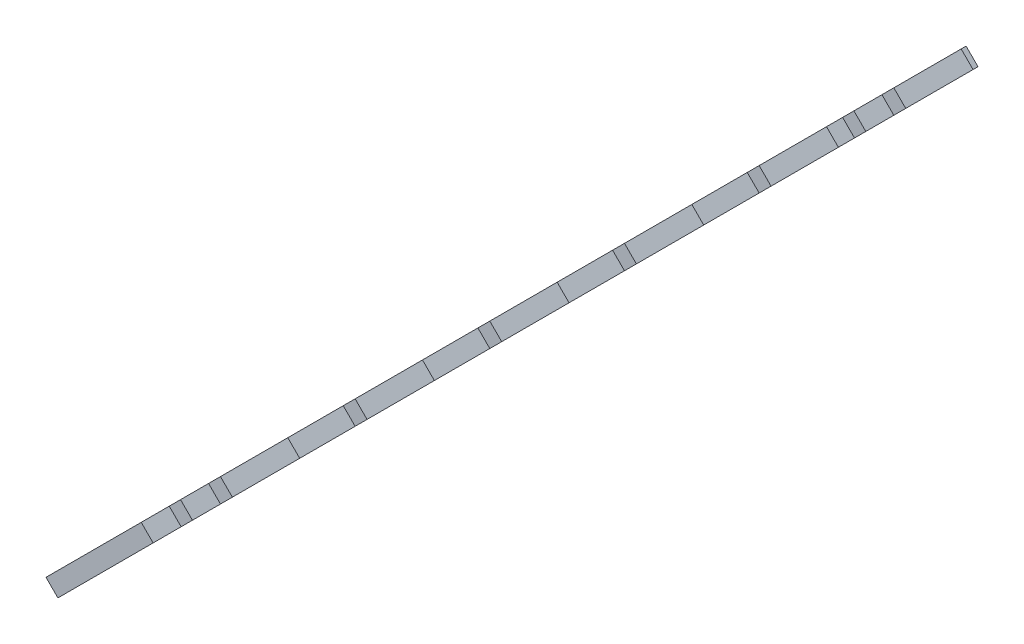
SolidWorks part; units mm, degrees
ref_plane "Front Plane" through (0, 0, 0) normal (0, 0, 1) x (1, 0, 0)
ref_plane "Top Plane" through (0, 0, 0) normal (0, 1, 0) x (1, 0, 0)
ref_plane "Right Plane" through (0, 0, 0) normal (1, 0, 0) x (0, 0, -1)
sketch "Sketch1" plane through (0, 0, 0) normal (0, 0, 1) x (1, 0, 0)
  line L0 (91.6648, 29.3027) -> (52.5461, -9.816) construction
  line L2 (78.5772, 20.7053) -> (74.1015, 16.2295) construction
  line L3 (78.5917, 11.7394) -> (83.0674, 16.2151) construction
  line L4 (37.7171, 7.6839) -> (33.2269, 12.174)
  line L5 (37.7171, 7.6839) -> (73.6381, 43.6049)
  line L6 (33.2269, 12.174) -> (69.148, 48.095)
  line L7 (73.6381, 43.6049) -> (69.148, 48.095)
  line L8 (110.4572, 6.7859) -> (74.5361, -29.1352) construction
  line L9 (74.5361, -29.1352) -> (70.046, -24.645) construction
  line L10 (105.967, 11.276) -> (70.046, -24.645) construction
extrude "Boss-Extrude1" add sketch "Sketch1" along normal up to surface (304.8 mm away)
sketch "Sketch2" plane through (58.6215, 58.6215, 0) normal (0.7071, 0.7071, 0) x (0, 0, -1)
  line L0 (-304.8, -21.2367) -> (0, -21.2367) construction
  line L1 (-279.4, -21.2367) -> (-254, -21.2367)
  line L2 (-279.4, -21.2367) -> (-279.4, -14.8867)
  line L3 (-279.4, -14.8867) -> (-254, -14.8867)
  line L4 (-254, -21.2367) -> (-254, -14.8867)
  line L5 (-304.8, -14.8867) -> (0, -14.8867) construction
  dimension "D1" = 25.4
  dimension "D2" = 25.4
extrude "Boss-Extrude2" add sketch "Sketch2" along normal blind 6.35
pattern_linear "LPattern1" count 6 spacing 50.8 along (0, 0, -1) of "Boss-Extrude2"
sketch "Sketch3" plane through (15.0166, -15.0166, 0) normal (0.7071, -0.7071, 0) x (0, 0, -1)
  circle A0 centre (-273.3375, 57.5033) radius 1.25
  dimension "D1" = 2.5
extrude "Cut-Extrude1" cut sketch "Sketch3" against normal up to surface (6.35 mm away) up to face at (68.6299, 47.5769, 155.3308)
sketch "Sketch4" plane through (0, 0, 0) normal (0, 0, -1) x (-1, 0, 0)
  line L0 (-33.2269, 12.174) -> (-37.7171, 7.6839)
  line L1 (-73.6381, 52.5852) -> (-33.2269, 12.174) construction
  line L2 (-37.7171, 7.6839) -> (-78.1282, 48.095) construction
  line L3 (-37.7171, 7.6839) -> (-46.6973, 16.6641)
  line L4 (-46.6973, 16.6641) -> (-42.2072, 21.1543)
  line L5 (-42.2072, 21.1543) -> (-33.2269, 12.174)
  dimension "D1" = 12.7
  dimension "D2" = 0
  dimension "D3" = 6.35
extrude "Boss-Extrude3" add sketch "Sketch4" along normal blind 6.35
pattern_linear "LPattern2" count 2 spacing 38.1 along (0.7071, 0.7071, 0) of "Boss-Extrude3"
sketch "Sketch5" plane through (10.5265, -10.5265, 0) normal (-0.7071, 0.7071, 0) x (0.7071, 0.7071, 0)
  line L0 (57.5033, -7.2251) -> (57.5033, -39.5117) construction
  line L1 (44.8033, 6.35) -> (44.8033, 0) construction
  line L2 (70.2033, 6.35) -> (70.2033, 0) construction
  line L3 (70.2033, 0) -> (44.8033, 0) construction
  line B0 (59.6369, 0) -> (55.3697, 0)
  line B1 (55.3697, -11.938) -> (53.0583, -11.938)
  line B2 (53.0583, -11.938) -> (53.0583, -8.763)
  line B3 (53.0583, -8.763) -> (55.3697, -8.763)
  line B4 (55.3697, -8.763) -> (55.3697, 0)
  line B5 (55.3697, -11.938) -> (55.3697, -15.24)
  line B6 (55.3697, -15.24) -> (59.6369, -15.24)
  line B7 (59.6369, -11.938) -> (59.6369, -15.24)
  line B8 (59.6369, -8.763) -> (59.6369, 0)
  line B9 (61.9483, -8.763) -> (59.6369, -8.763)
  line B10 (61.9483, -11.938) -> (61.9483, -8.763)
  line B11 (59.6369, -11.938) -> (61.9483, -11.938)
sketch_block_instance "TSlot-1"
sketch_block "TSlot" parameters "D1"=3.302, "D2"=3.175
extrude "Cut-Extrude2" cut sketch "Sketch5" against normal through all
sketch "Sketch6" plane through (10.5265, -10.5265, 0) normal (-0.7071, 0.7071, 0) x (0.7071, 0.7071, 0)
  line L0 (82.9033, -292.1) -> (47.6349, -292.1) construction
  line L1 (82.9033, -304.8) -> (82.9033, -279.4) construction
  line L4 (82.9033, -38.1) -> (53.7612, -38.1) construction
  line L5 (82.9033, -50.8) -> (82.9033, -25.4) construction
  line L6 (89.2533, -25.4) -> (82.9033, -25.4) construction
  line L7 (89.2533, -50.8) -> (82.9033, -50.8) construction
  line L10 (89.2533, -279.4) -> (82.9033, -279.4) construction
  line L11 (32.1033, -304.8) -> (82.9033, -304.8) construction
  line B0 (82.9033, -294.2336) -> (82.9033, -289.9664)
  line B1 (70.9653, -289.9664) -> (70.9653, -287.655)
  line B2 (70.9653, -287.655) -> (74.1403, -287.655)
  line B3 (74.1403, -287.655) -> (74.1403, -289.9664)
  line B4 (74.1403, -289.9664) -> (82.9033, -289.9664)
  line B5 (70.9653, -289.9664) -> (67.6633, -289.9664)
  line B6 (67.6633, -289.9664) -> (67.6633, -294.2336)
  line B7 (70.9653, -294.2336) -> (67.6633, -294.2336)
  line B8 (74.1403, -294.2336) -> (82.9033, -294.2336)
  line B9 (74.1403, -296.545) -> (74.1403, -294.2336)
  line B10 (70.9653, -296.545) -> (74.1403, -296.545)
  line B11 (70.9653, -294.2336) -> (70.9653, -296.545)
  line B12 (82.9033, -40.2336) -> (82.9033, -35.9664)
  line B13 (70.9653, -35.9664) -> (70.9653, -33.655)
  line B14 (70.9653, -33.655) -> (74.1403, -33.655)
  line B15 (74.1403, -33.655) -> (74.1403, -35.9664)
  line B16 (74.1403, -35.9664) -> (82.9033, -35.9664)
  line B17 (70.9653, -35.9664) -> (67.6633, -35.9664)
  line B18 (67.6633, -35.9664) -> (67.6633, -40.2336)
  line B19 (70.9653, -40.2336) -> (67.6633, -40.2336)
  line B20 (74.1403, -40.2336) -> (82.9033, -40.2336)
  line B21 (74.1403, -42.545) -> (74.1403, -40.2336)
  line B22 (70.9653, -42.545) -> (74.1403, -42.545)
  line B23 (70.9653, -40.2336) -> (70.9653, -42.545)
sketch_block_instance "TSlot-2"
sketch_block_instance "TSlot-4"
extrude "Cut-Extrude3" cut sketch "Sketch6" against normal through all
sketch "Sketch7" plane through (15.0166, -15.0166, 0) normal (0.7071, -0.7071, 0) x (-0.7071, -0.7071, 0)
  line L0 (-89.2533, -213.6951) -> (-82.9033, -217.9623) construction
  line L1 (-82.9033, -213.6951) -> (-89.2533, -217.9623) construction
  line L2 (-89.2533, -228.6) -> (-89.2533, -203.2) construction
  line L3 (-89.2533, -217.9623) -> (-82.9033, -217.9623) construction
  line L4 (-89.2533, -65.5623) -> (-82.9033, -61.2951) construction
  line L5 (-89.2533, -65.5623) -> (-82.9033, -65.5623) construction
  line L6 (-89.2533, -76.2) -> (-89.2533, -50.8) construction
  line L7 (-82.9033, -65.5623) -> (-89.2533, -61.2951) construction
  line L8 (-82.9033, -61.2951) -> (-89.2533, -61.2951) construction
  circle A0 centre (-86.0783, -215.8287) radius 2.0955
  circle A1 centre (-86.0783, -63.4287) radius 2.0955
  dimension "D1" = 4.191
extrude "Cut-Extrude4" cut sketch "Sketch7" against normal through all
sketch "Sketch8" plane through (10.5265, -10.5265, 0) normal (-0.7071, 0.7071, 0) x (0.7071, 0.7071, 0)
  line L0 (32.1033, -304.8) -> (32.1033, 6.35) construction
  line L1 (32.1033, -133.35) -> (63.8533, -133.35)
  line L2 (32.1033, -133.35) -> (32.1033, -196.85)
  line L3 (32.1033, -196.85) -> (63.8533, -196.85)
  line L4 (63.8533, -133.35) -> (63.8533, -196.85)
  line L5 (55.3697, 0) -> (44.8033, 0) construction
  dimension "D1" = 133.35
  dimension "D2" = 63.5
  dimension "D3" = 31.75
extrude "Cut-Extrude5" cut sketch "Sketch8" against normal through all
fillet "Fillet1" radius 3.81 4 edges at (57.9227, 32.3796, 196.85) (57.9227, 32.3796, 133.35) (35.472, 9.9289, 196.85) (35.472, 9.9289, 133.35)
